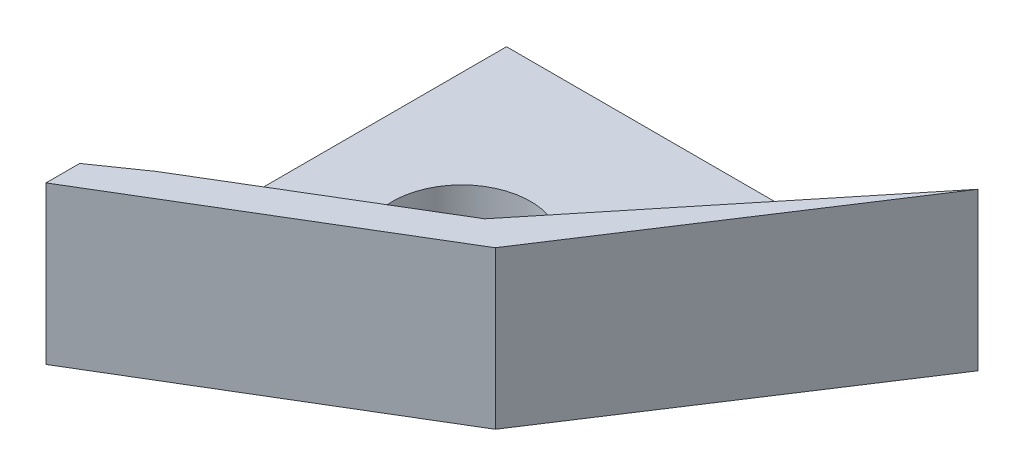
SolidWorks part; units mm, degrees
ref_plane "Front Plane" through (0, 0, 0) normal (0, 0, 1) x (1, 0, 0)
ref_plane "Top Plane" through (0, 0, 0) normal (0, 1, 0) x (1, 0, 0)
ref_plane "Right Plane" through (0, 0, 0) normal (1, 0, 0) x (0, 0, -1)
sketch "Sketch1" plane through (0, 0, 0) normal (0, 1, 0) x (1, 0, 0)
  line L1 (69.8823, -141.1569) -> (82.3823, -133.6569)
  line L8 (69.8823, -141.1569) -> (69.8823, -120.6569)
  line L11 (69.8823, -120.6569) -> (90.8715, -120.6569)
  line L13 (90.8715, -120.6569) -> (82.3823, -133.6569)
  circle A0 centre (76.3823, -129.1569) radius 3.075
  dimension "D2" = 6.15
  dimension "D3" = 20.5
  dimension "D1" = 8.5
  dimension "D4" = 4.5
  dimension "D5" = 6
  dimension "D6" = 20.9892
  dimension "D7" = 6.5
extrude "Boss-Extrude1" add sketch "Sketch1" along normal blind 2
sketch "Sketch2" plane through (0, 0, 0) normal (0, -1, 0) x (-1, 0, 0)
  line L0 (-69.8823, -141.1569) -> (-82.3823, -133.6569)
  line L1 (-82.3823, -133.6569) -> (-90.8715, -120.6569)
  line L3 (-71.8823, -138.268) -> (-69.8823, -139.6569)
  line L4 (-69.8823, -120.6569) -> (-69.8823, -141.1569) construction
  line L5 (-69.8823, -139.6569) -> (-69.8823, -141.1569)
  line L6 (-71.8823, -138.268) -> (-81.0344, -132.7767)
  line L7 (-81.0344, -132.7767) -> (-90.8715, -120.6569)
  dimension "D1" = 1.5
  dimension "D2" = 2
extrude "Boss-Extrude2" add sketch "Sketch2" against normal blind 7
